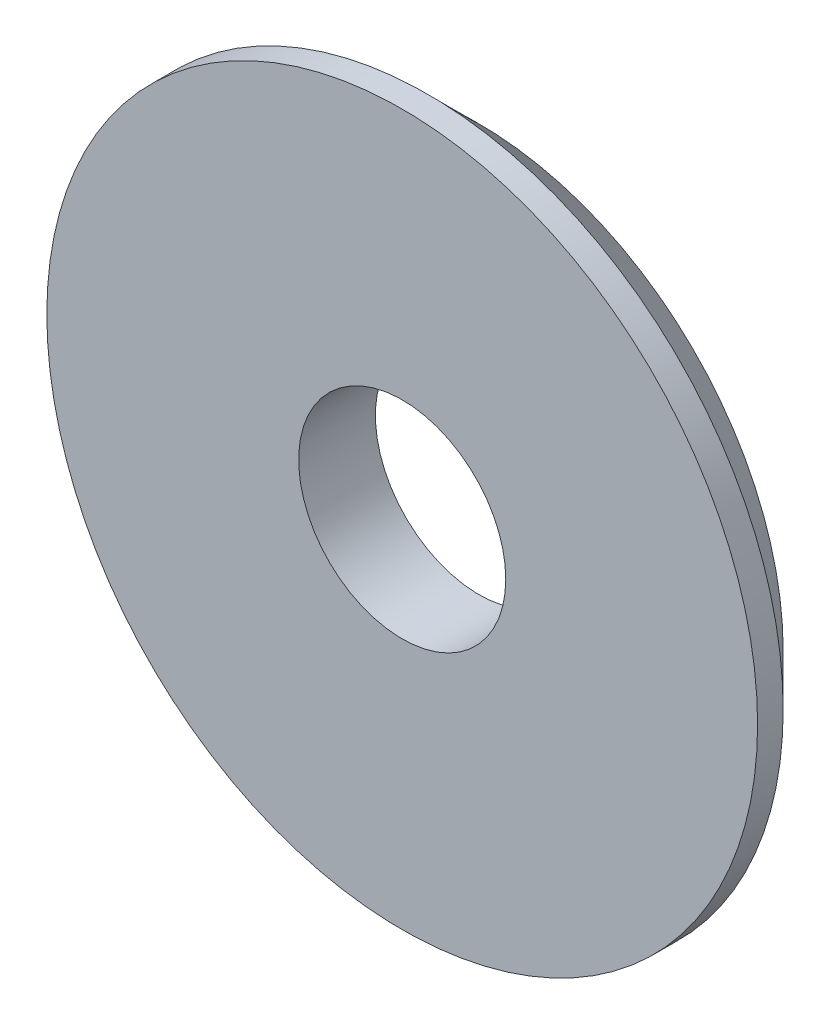
SolidWorks part; units mm, degrees
ref_plane "前视基准面" through (0, 0, 0) normal (0, 0, 1) x (1, 0, 0)
ref_plane "上视基准面" through (0, 0, 0) normal (0, 1, 0) x (1, 0, 0)
ref_plane "右视基准面" through (0, 0, 0) normal (1, 0, 0) x (0, 0, -1)
sketch "草图1" plane through (0, 0, 0) normal (0, 0, 1) x (1, 0, 0)
  circle A0 centre (0, 0) radius 4.05
  circle A1 centre (0, 0) radius 13.9
  dimension "D1" = 8.1
  dimension "D2" = 27.8
extrude "凸台-拉伸1" add sketch "草图1" along normal blind 3
chamfer "倒角1" distance 2 angle 45 1 edges at (13.9, 0, 0)
